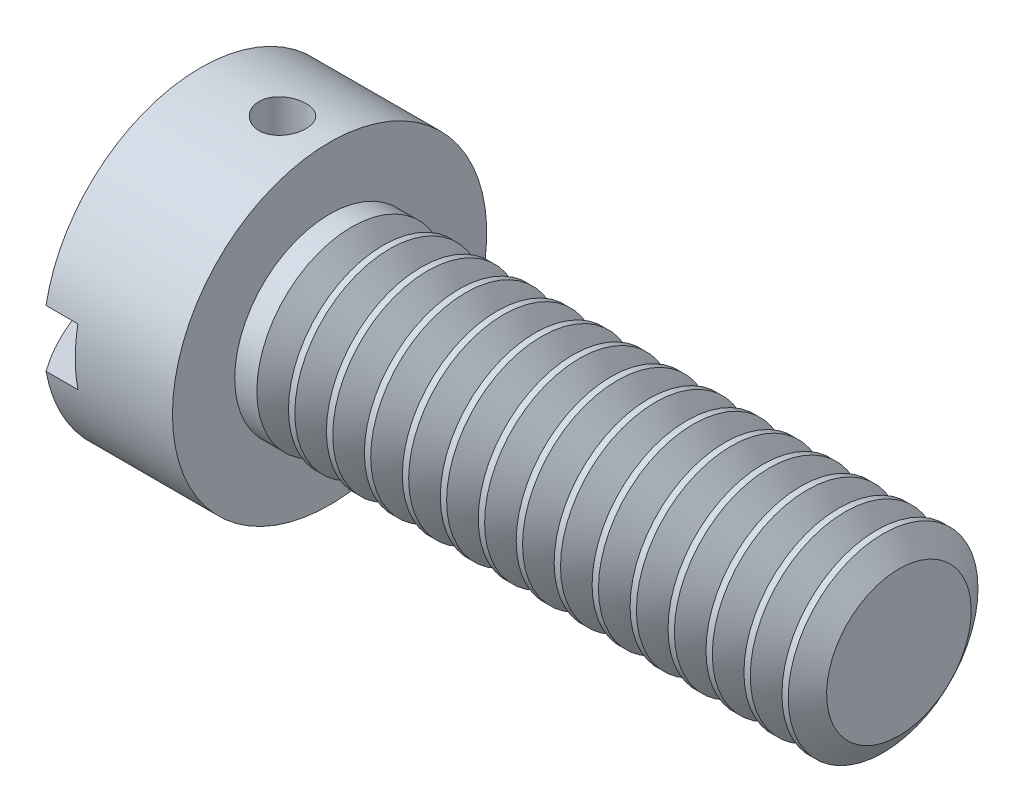
SolidWorks part; units mm, degrees
ref_plane "Plane1" through (0, 0, 0) normal (0, 0, 1) x (1, 0, 0)
ref_plane "Plane2" through (0, 0, 0) normal (0, 1, 0) x (1, 0, 0)
ref_plane "Plane3" through (0, 0, 0) normal (1, 0, 0) x (0, 0, -1)
sketch "BodySke" plane through (0, 0, 0) normal (0, 0, 1) x (1, 0, 0)
  line L0 (6.0198, 3.175) -> (6.0198, 5.2578)
  line L1 (6.0198, 5.2578) -> (1.7018, 5.2578)
  line L2 (-25.4, 0) -> (127, 0) construction
  line L3 (25.0698, 0) -> (0, 0)
  line L4 (6.0198, 3.175) -> (25.0698, 3.175)
  line L5 (25.0698, 3.175) -> (25.0698, 0)
  line L6 (6.0198, -5.2578) -> (1.7018, -5.2578) construction
  line L7 (6.0198, -3.175) -> (25.0698, -3.175) construction
  line L8 (7.2898, 1.2192) -> (7.2898, -0.4698) construction
  line L9 (6.0198, 1.2192) -> (6.0198, -0.4698) construction
  arc A0 (0, 0) -> (1.7018, 5.2578) centre (8.973, 0) cw
  dimension "Diameter" = 6.35
  dimension "Head_dia" = 10.5156
  dimension "Head_ht" = 6.0198
  dimension "Head_side_ht" = 4.318
  dimension "Advance" = 1.27
revolve "Base-Revolve" add sketch "BodySke" angle 360 about L2
cosmetic thread "ThreadCosmetic" [suppressed] parameters "Thread_length"=14.605, "Thread_minor"=4.8387
sketch "Sketch2" plane through (0, 0, 0) normal (1, 0, 0) x (0, 0, -1)
  line L0 (-5.2578, -0.9525) -> (-5.2578, 0.9525)
  line L1 (-5.2578, 0.9525) -> (5.2578, 0.9525)
  line L2 (5.2578, 0.9525) -> (5.2578, -0.9525)
  line L3 (5.2578, -0.9525) -> (-5.2578, -0.9525)
  dimension "D1" = 10.5156
  dimension "D2" = 5.2578
  dimension "D3" = 0.9525
  dimension "Slot_width" = 1.905
extrude "Slot" cut sketch "Sketch2" along normal blind 2.7686
sketch "Sketch3" plane through (0, 0, 0) normal (1, 0, 0) x (0, 0, -1)
  line L0 (0.6858, -3.9116) -> (-0.6858, -3.9116)
  line L1 (0.6858, -3.9116) -> (0.6858, 3.9116)
  line L2 (-0.6858, 3.9116) -> (0.6858, 3.9116)
  line L3 (-0.6858, 3.9116) -> (-0.6858, -3.9116)
  dimension "Cross_width" = 1.3716
  dimension "D1" = 0.6858
  dimension "Cross_dia" = 7.8232
  dimension "D2" = 3.9116
ref_plane "Plane4" through (4.6228, 0, 0) normal (1, 0, 0) x (0, 0, -1)
sketch "Sketch4" plane through (4.6228, 0, 0) normal (1, 0, 0) x (0, 0, -1)
  line L0 (0.3429, -0.3429) -> (-0.3429, -0.3429)
  line L1 (0.3429, -0.3429) -> (0.3429, 0.3429)
  line L2 (-0.3429, 0.3429) -> (0.3429, 0.3429)
  line L3 (-0.3429, 0.3429) -> (-0.3429, -0.3429)
  dimension "D1" = 0.6858
  dimension "D2" = 0.3429
  dimension "D3" = 0.6858
  dimension "D4" = 0.3429
loft "Cross" [suppressed] cut profiles "Sketch3", "Sketch4"
pattern_circular "CirPattern1" [suppressed] count 2 every 90 about axis through (-25.4, 0, 0) along (1, 0, 0)
sketch "Sketch5" plane through (0, 0, 0) normal (0, 1, 0) x (1, 0, 0)
  line L4 (-25.4, 0) -> (127, 0) construction
  line L5 (6.0198, -6.312) -> (6.0198, 6.3337) construction
  circle A0 centre (4.445, 0) radius 0.7874
  dimension "Drilled_hole_dia" = 1.5748
  dimension "D1" = 6.0198
  dimension "Drilled_hole_loc" = 1.5748
extrude "Hole" cut sketch "Sketch5" against normal through all and the other way through all
sketch "ThdSchSke" plane through (0, 0, 0) normal (0, 0, 1) x (1, 0, 0)
  line L0 (7.2898, -2.4193) -> (6.7607, -3.175)
  line L1 (7.2898, -2.4193) -> (7.8189, -3.175)
  line L2 (7.8189, -3.175) -> (7.8189, -3.9687)
  line L3 (-3.175, 0) -> (5.1513, 0) construction
  line L5 (7.8189, -3.9687) -> (6.7607, -3.9687)
  line L6 (6.7607, -3.9687) -> (6.7607, -3.175)
  dimension "Diameter" = 6.35
  dimension "SideAngle" = 55
  dimension "VeeAngle" = 70
  dimension "Thread_minor" = 4.8387
  dimension "Overcut" = 7.9375
  dimension "Start" = 7.2898
revolve "ThreadSchematic" cut sketch "ThdSchSke" angle 360 about L3
pattern_linear "ThdSchPat" count 15 spacing 1.27 along (1, 0, 0) of "ThreadSchematic"
equation "\"D1@Sketch3\" = \"Cross_width@Sketch3\" / 2"
equation "\"D2@Sketch3\" = \"Cross_dia@Sketch3\" / 2"
equation "\"D1@Sketch4\" = \"Cross_width@Sketch3\"*.5"
equation "\"D2@Sketch4\" = \"D1@Sketch4\" / 2"
equation "\"D3@Sketch4\" = \"D1@Sketch4\""
equation "\"D4@Sketch4\" = \"D2@Sketch4\""
equation "\"D1@Sketch2\" = \"Head_dia@BodySke\""
equation "\"D2@Sketch2\" = \"D1@Sketch2\" / 2"
equation "\"D3@Sketch2\" = \"Slot_width@Sketch2\" / 2"
equation "\"D1@Sketch5\" = \"Head_ht@BodySke\""
equation "\"Thread_length@ThreadCosmetic\" = ((sgn( (\"Length@BodySke\" - \"Advance@BodySke\" ) - \"Thread_nom@BodySke\" )-1)*( (\"Length@BodySke\" - \"Advance@BodySke\" ) - \"Thread_nom@BodySke\" ))/-2+ \"Thread_nom@BodySke\""
equation "\"Thread_minor@ThdSchSke\" = \"Thread_minor@ThreadCosmetic\""
equation "\"Diameter@ThdSchSke\" = \"Diameter@BodySke\""
equation "\"Overcut@ThdSchSke\" = \"Diameter@BodySke\" * 1.25"
equation "\"Start@ThdSchSke\" = \"Head_ht@BodySke\" + \"Length@BodySke\" - \"Thread_length@ThreadCosmetic\"  '---Non-countersunk---"
equation "\"Num_threads@ThdSchPat\" = int( \"Thread_length@ThreadCosmetic\" / \"Advance@BodySke\" + 0.999 )  + 1"
equation "\"Advance@ThdSchPat\" = \"Thread_length@ThreadCosmetic\" /  (\"Num_threads@ThdSchPat\" - 1) 'relax it"
